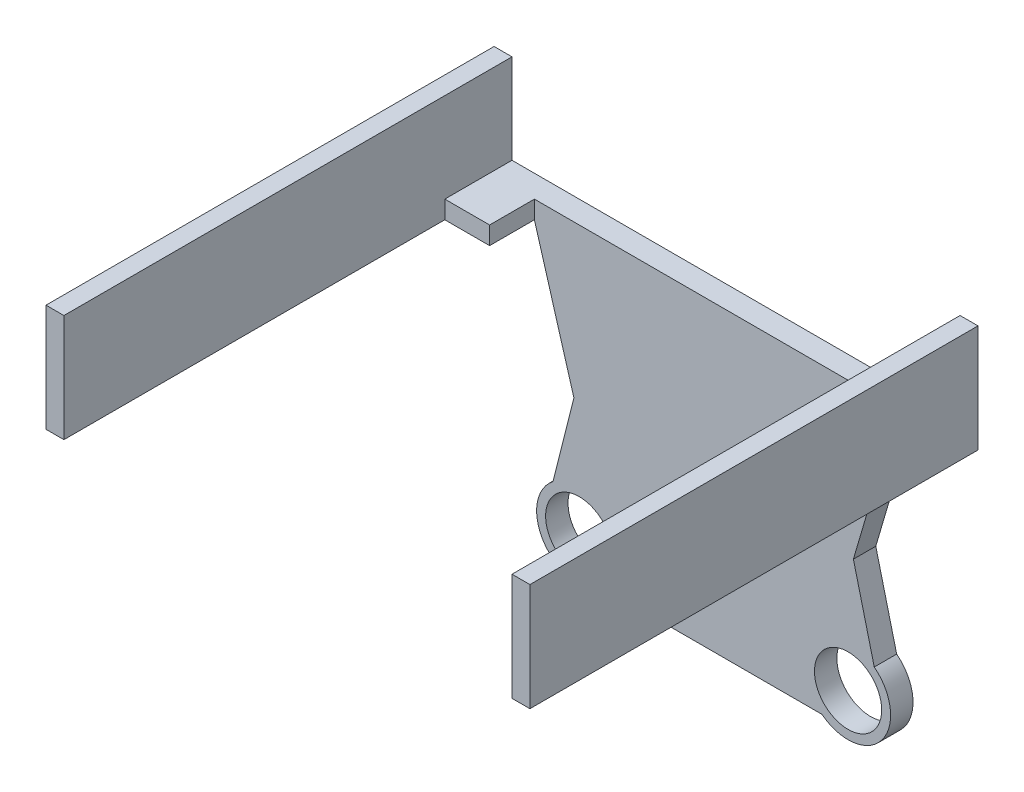
SolidWorks part; units mm, degrees
ref_plane "Front Plane" through (0, 0, 0) normal (0, 0, 1) x (1, 0, 0)
ref_plane "Top Plane" through (0, 0, 0) normal (0, 1, 0) x (1, 0, 0)
ref_plane "Right Plane" through (0, 0, 0) normal (1, 0, 0) x (0, 0, -1)
sketch "Sketch1" plane through (0, 0, 0) normal (0, 0, 1) x (1, 0, 0)
  line L0 (-25, 215) -> (-20, 215) construction
  line L1 (-25, 215) -> (-25, 225) construction
  line L2 (-20, 225) -> (-25, 225) construction
  line L3 (20, 225) -> (-20, 225) construction
  line L4 (25, 225) -> (20, 225) construction
  line L5 (25, 225) -> (25, 215) construction
  line L6 (20, 215) -> (25, 215) construction
  line L7 (20, 215) -> (-20, 215) construction
  line L8 (-25, 215) -> (-20, 215)
  line L9 (-25, 215) -> (-25, 225)
  line L10 (-20, 225) -> (-25, 225)
  line L11 (20, 225) -> (-20, 225)
  line L12 (25, 225) -> (20, 225)
  line L13 (25, 225) -> (25, 215)
  line L14 (20, 215) -> (25, 215)
  line L15 (20, 215) -> (-20, 215)
  line L16 (27, 225) -> (27, 213)
  line L17 (20, 213) -> (27, 213)
  line L18 (20, 213) -> (-20, 213) construction
  line L19 (-27, 213) -> (-20, 213)
  line L20 (-27, 213) -> (-27, 225)
  line L21 (-25, 225) -> (-27, 225)
  line L23 (25, 225) -> (27, 225)
  line L24 (-15.5941, 198) -> (15.5941, 198) construction
  line L25 (-15.5941, 198) -> (-17.9247, 188.7428)
  line L27 (-12.0845, 181.25) -> (12.0845, 181.25)
  line L29 (-20, 213) -> (-15.5941, 198)
  line L30 (20, 213) -> (15.5941, 198)
  line L31 (15.5941, 198) -> (17.9247, 188.7428)
  circle A0 centre (15, 185) radius 3.75 construction
  circle A1 centre (-15, 185) radius 3.75 construction
  arc A2 (15, 181.25) -> (18.6365, 185.9155) centre (15, 185) ccw
  arc A3 (-18.6365, 185.9155) -> (-15, 181.25) centre (-15, 185) ccw
  circle A4 centre (15, 185) radius 3.75
  circle A5 centre (-15, 185) radius 3.75
  arc A6 (-17.9247, 188.7428) -> (-12.0845, 181.25) centre (-15, 185) ccw
  arc A7 (12.0845, 181.25) -> (17.9247, 188.7428) centre (15, 185) ccw
  circle A9 centre (-15, 185) radius 4.75 construction
  circle A10 centre (15, 185) radius 4.75 construction
  point P14 (-27, 213)
  point P15 (-27, 227)
  point P18 (27, 227)
  point P19 (27, 213)
  point P25 (0, 0)
  point P26 (0, 0)
  point P28 (0, 0)
  point P31 (0, 0)
  point P35 (19.75, 185)
  point P39 (-10.4576, 186.3888)
  dimension "D2" = 149.5
  dimension "D3" = 149.5
  dimension "D4" = 15
  dimension "D5" = 1
  dimension "D1" = 2
  dimension "D6" = 1
extrude "Boss-Extrude1" add sketch "Sketch1" along normal blind 2.5 contours L25 A3 L27 A2 L31 L30 L17 L16 L23 L13 L14 L15 L8 L9 L21 L20 L19 L29
sketch "Sketch2" plane through (0, 225, 0) normal (0, 1, 0) x (1, 0, 0)
  line L0 (25, -5) -> (25, -45) construction
  line L1 (27, -2.5) -> (25, -2.5)
  line L2 (27, -2.5) -> (27, -50)
  line L3 (27, -50) -> (25, -50)
  line L4 (25, -2.5) -> (25, -50)
  line L5 (-27, -2.5) -> (-25, -2.5)
  line L6 (-27, -2.5) -> (-27, -50)
  line L7 (-27, -50) -> (-25, -50)
  line L8 (-25, -2.5) -> (-25, -50)
  line L9 (-25, -45) -> (-25, -5) construction
  line L10 (20, -50) -> (-20, -50) construction
extrude "Boss-Extrude2" add sketch "Sketch2" against normal up to surface (12 mm away) up to face at (23.5, 213, 1.25)
sketch "Sketch3" plane through (0, 0, 2.5) normal (0, 0, 1) x (1, 0, 0)
  line L0 (-25, 215) -> (25, 215) construction
  line L1 (-25, 213) -> (-20, 213)
  line L2 (-25, 213) -> (-25, 215)
  line L3 (-25, 215) -> (-20, 215)
  line L4 (-20, 213) -> (-20, 215)
  line L5 (-20, 225) -> (-20, 215) construction
  line L7 (25, 213) -> (20, 213)
  line L8 (25, 213) -> (25, 215)
  line L9 (25, 215) -> (20, 215)
  line L10 (20, 213) -> (20, 215)
  point P14 (21.0265, 215)
extrude "Boss-Extrude3" add sketch "Sketch3" along normal blind 5
